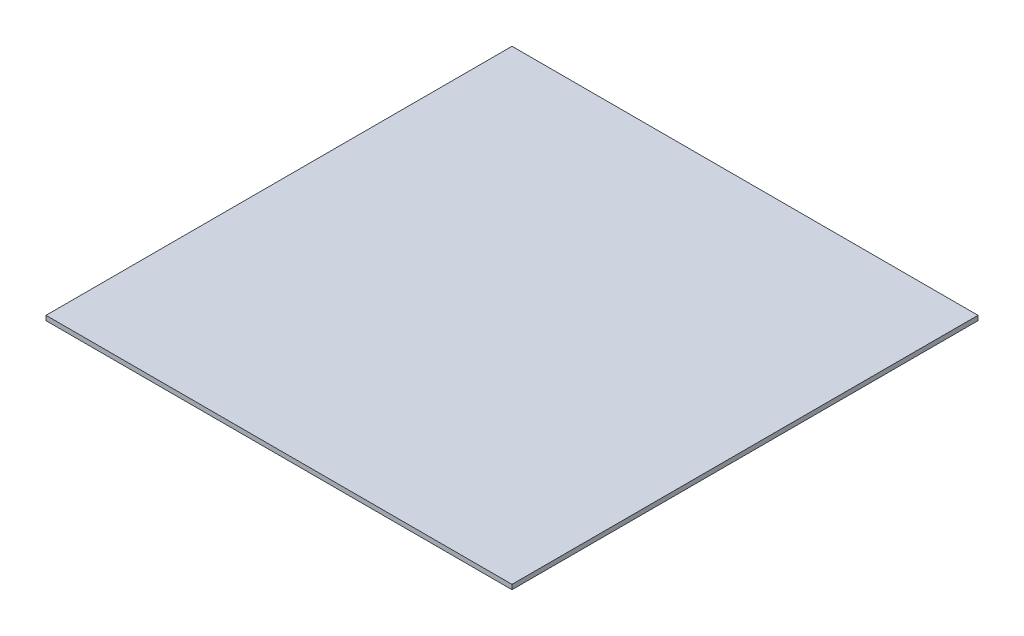
SolidWorks part; units mm, degrees
ref_plane "Front Plane" through (0, 0, 0) normal (0, 0, 1) x (1, 0, 0)
ref_plane "Top Plane" through (0, 0, 0) normal (0, 1, 0) x (1, 0, 0)
ref_plane "Right Plane" through (0, 0, 0) normal (1, 0, 0) x (0, 0, -1)
sketch "Sketch1" plane through (0, 0, 0) normal (0, 1, 0) x (1, 0, 0)
  line L1 (-100, 100) -> (100, 100)
  line L2 (-100, 100) -> (-100, -100)
  line L3 (-100, -100) -> (100, -100)
  line L4 (100, 100) -> (100, -100)
  line L5 (-100, 100) -> (100, -100) construction
  line L6 (-100, -100) -> (100, 100) construction
  point P0 (0, 0)
  dimension "D1" = 200
  dimension "D2" = 200
extrude "Boss-Extrude1" add sketch "Sketch1" along normal blind 2
